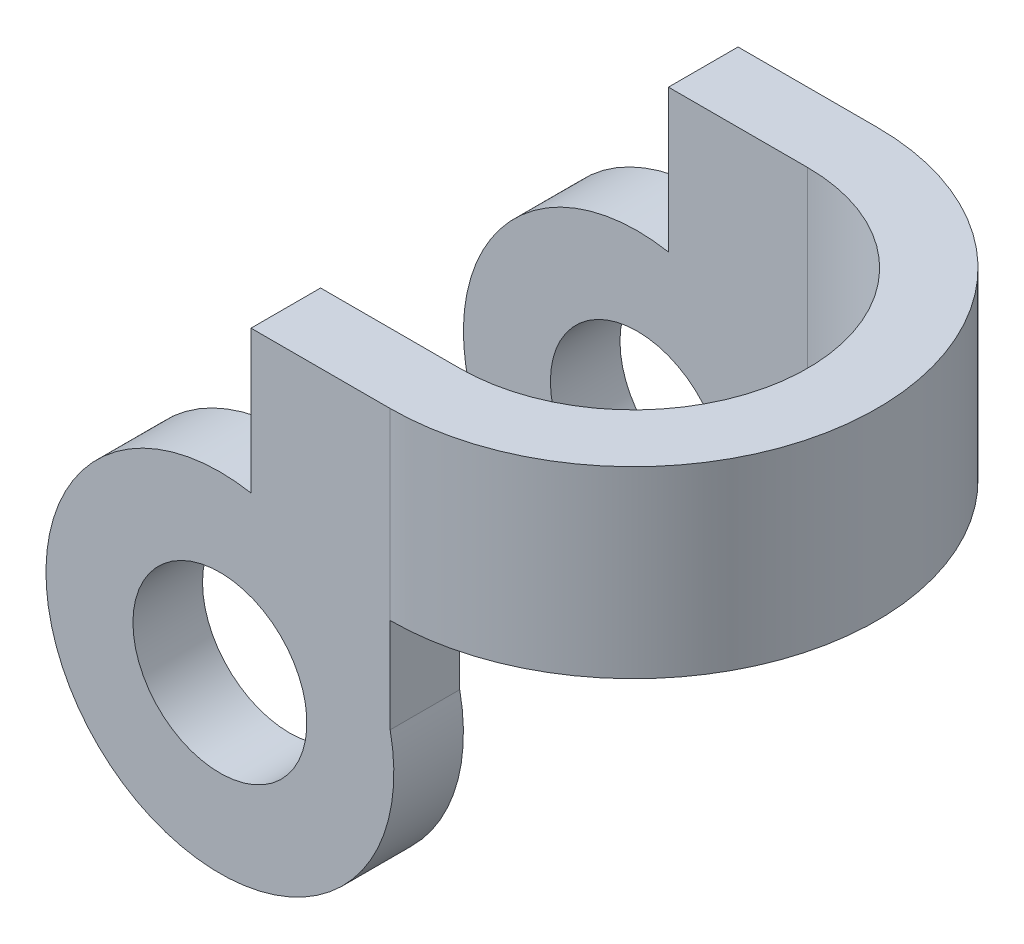
SolidWorks part; units mm, degrees
ref_plane "Front Plane" through (0, 0, 0) normal (0, 0, 1) x (1, 0, 0)
ref_plane "Top Plane" through (0, 0, 0) normal (0, 1, 0) x (1, 0, 0)
ref_plane "Right Plane" through (0, 0, 0) normal (1, 0, 0) x (0, 0, -1)
sketch "Sketch1" plane through (0, 0, 0) normal (0, 0, 1) x (1, 0, 0)
  circle A0 centre (0, 0) radius 12.5
  dimension "D1" = 25
extrude "Boss-Extrude1" add sketch "Sketch1" along normal blind 5
ref_plane "Plane1" through (0, 0, 30) normal (0, 0, 1) x (1, 0, 0)
sketch "Sketch2" plane through (0, 0, 30) normal (0, 0, 1) x (1, 0, 0)
  circle A0 centre (0, 0) radius 12.5
extrude "Boss-Extrude2" add sketch "Sketch2" along normal blind 5 separate body contours A0
sketch "Sketch4" plane through (0, 0, 5) normal (0, 0, 1) x (1, 0, 0)
  line L0 (12.2353, 2.5586) -> (2.2353, 2.5586)
  line L1 (2.2353, 2.5586) -> (2.2353, 22.5586)
  line L2 (12.2353, 2.5586) -> (12.2353, 22.5586)
  line L3 (12.2353, 22.5586) -> (2.2353, 22.5586)
  circle A0 centre (0, 0) radius 12.5 construction
  dimension "D1" = 20
  dimension "D2" = 10
extrude "Boss-Extrude4" add sketch "Sketch4" against normal blind 5
ref_plane "Plane2" through (0, 0, 13) normal (0, 0, 1) x (1, 0, 0)
sketch "Sketch5" plane through (0, 0, 30) normal (0, 0, -1) x (-1, 0, 0)
  line L0 (-12.2353, 2.5586) -> (-12.2353, 22.5586)
  line L1 (-12.2353, 22.5586) -> (-2.2353, 22.5586)
  line L2 (-2.2353, 22.5586) -> (-2.2353, 2.5586)
  line L3 (-2.2353, 2.5586) -> (-12.2353, 2.5586)
extrude "Boss-Extrude5" add sketch "Sketch5" against normal blind 5
sketch "Sketch8" plane through (0, 0, 0) normal (0, 0, -1) x (-1, 0, 0)
  circle A0 centre (0, 0) radius 6.25
  dimension "D1" = 12.5
extrude "Cut-Extrude2" cut sketch "Sketch8" against normal blind 35
sketch "Sketch12" plane through (12.2353, 0, 0) normal (1, 0, 0) x (0, 0, -1)
  line L0 (-30, 22.5586) -> (-30, 2.5586) construction
  line L1 (-35, 22.5586) -> (-30, 22.5586)
  line L2 (-35, 22.5586) -> (-35, 9.3629)
  line L3 (-35, 9.3629) -> (-30, 9.3629)
  line L4 (-30, 22.5586) -> (-30, 9.3629)
  line L5 (-35, 22.5586) -> (-30, 9.3629)
  point P7 (-32.5, 15.9608)
ref_plane "Plane4" through (0, 15.9608, 0) normal (0, 1, 0) x (1, 0, 0)
sketch "Sketch14" plane through (0, 15.9608, 0) normal (0, 1, 0) x (1, 0, 0)
  line L0 (12.2353, 0) -> (12.2353, -5) construction
  arc A0 (12.2353, -32.5) -> (12.2353, -2.5) centre (12.2353, -17.5) ccw
sweep "Sweep2" add profiles "Sketch12" path "Sketch14"
